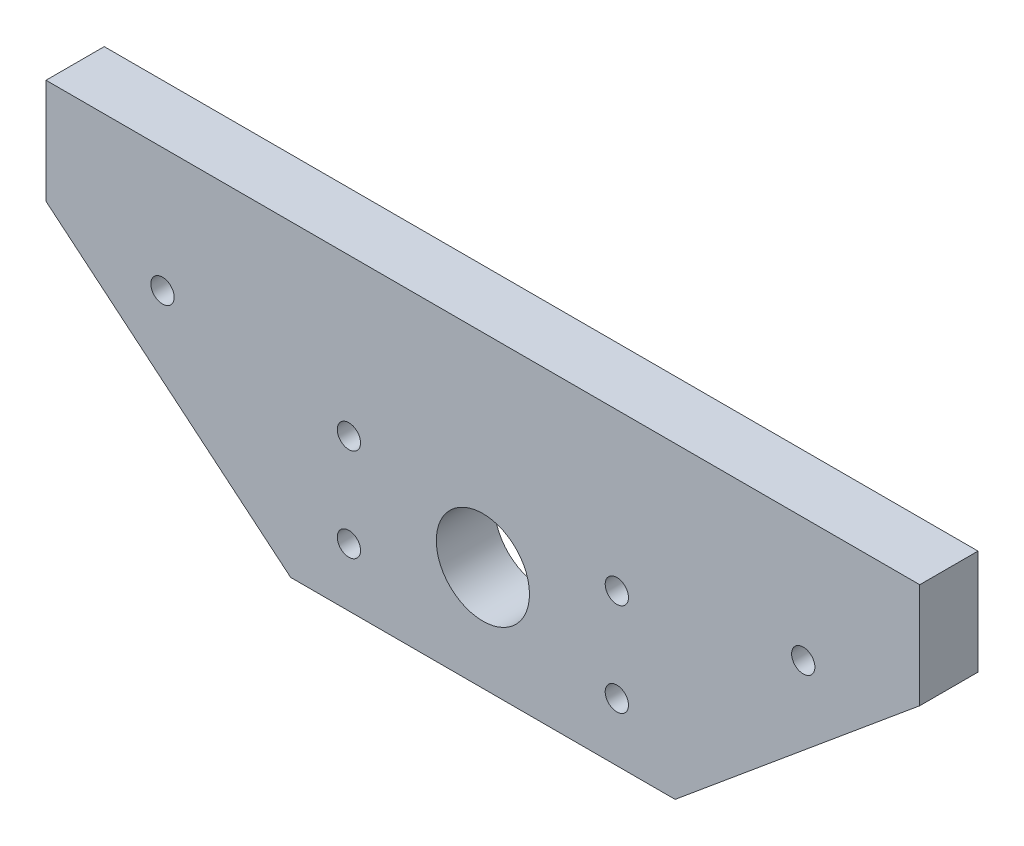
SolidWorks part; units mm, degrees
material "아크릴(내충격성)"
ref_plane "정면" through (0, 0, 0) normal (0, 0, 1) x (1, 0, 0)
ref_plane "윗면" through (0, 0, 0) normal (0, 1, 0) x (1, 0, 0)
ref_plane "우측면" through (0, 0, 0) normal (1, 0, 0) x (0, 0, -1)
sketch "스케치1" plane through (0, 0, 0) normal (0, 0, 1) x (1, 0, 0)
  line L1 (-75, 34.9192) -> (75, 34.9192)
  line L2 (-75, 34.9192) -> (-75, -35.0808)
  line L3 (-75, -35.0808) -> (75, -35.0808)
  line L4 (75, 34.9192) -> (75, -35.0808)
  line L5 (-75, 34.9192) -> (75, -35.0808) construction
  line L6 (-75, -35.0808) -> (75, 34.9192) construction
  dimension "D1" = 150
  dimension "D2" = 70
extrude "보스-돌출1" add sketch "스케치1" along normal blind 10
sketch "스케치2" plane through (0, 0, 10) normal (0, 0, 1) x (1, 0, 0)
  line L0 (75, 34.9192) -> (-75, 34.9192) construction
  line L1 (75, -35.0808) -> (75, 34.9192) construction
  line L2 (-75, -35.0808) -> (75, -35.0808) construction
  circle A0 centre (0, 0) radius 8
extrude "컷-돌출1" cut sketch "스케치2" against normal through all
sketch "스케치3" plane through (0, 0, 10) normal (0, 0, 1) x (1, 0, 0)
  line L0 (-56.0789, 0) -> (55.5902, 0) construction
  line L1 (0, 49.5425) -> (0, -49.6646) construction
  line L2 (-56.0789, -15) -> (55.5902, -15)
  line L3 (-56.0789, 15) -> (55.5902, 15)
  line L4 (-30, 49.5425) -> (-30, -49.6646)
  line L5 (30, 49.5425) -> (30, -49.6646)
  line L6 (75, 34.9192) -> (-75, 34.9192) construction
  circle A0 centre (-23, 8) radius 2
  circle A1 centre (-23, -8) radius 2
  circle A2 centre (23, -8) radius 2
  circle A3 centre (23, 8) radius 2
  dimension "D5" = 4
  dimension "D6" = 7
  dimension "D7" = 7
  dimension "D1" = 15
  dimension "D2" = 15
  dimension "D3" = 30
  dimension "D4" = 30
extrude "컷-돌출2" cut sketch "스케치3" against normal through all contours A0 | A1 | A2 | A3
sketch "스케치4" plane through (0, 0, 10) normal (0, 0, 1) x (1, 0, 0)
  line L0 (0, 49.097) -> (0, -61.2799) construction
  line L1 (-75, 34.9192) -> (-75, -35.0808) construction
  line L2 (-75, -35.0808) -> (75, -35.0808) construction
  line L3 (75, 34.9192) -> (-75, 34.9192) construction
  circle A0 centre (-55, 13.649) radius 2
  circle A1 centre (-65, -25.0808) radius 2
  circle A2 centre (65, -25.0808) radius 2
  circle A3 centre (55, 13.649) radius 2
  dimension "D1" = 4
  dimension "D2" = 4
  dimension "D3" = 10
  dimension "D4" = 10
  dimension "D5" = 20
  dimension "D6" = 40
extrude "컷-돌출3" cut sketch "스케치4" against normal through all
sketch "스케치5" plane through (0, 0, 10) normal (0, 0, 1) x (1, 0, 0)
  line L0 (-56.981, 13.9238) -> (56.981, 13.9238) construction
  line L1 (-65, -27.0808) -> (65, -27.0808) construction
  line L2 (-45, 25.7976) -> (-45, -31.7862) construction
  line L3 (-33, 24.5979) -> (-33, -29.3868) construction
  line L4 (33, 24.5979) -> (33, -29.3868) construction
  line L5 (45, 24.5979) -> (45, -30.7579) construction
  line L6 (-75, 16.9192) -> (-33, -18)
  line L16 (-75, 34.9192) -> (-75, -35.0808) construction
  line L18 (75, -35.0808) -> (75, 34.9192) construction
  line L19 (75, 16.9192) -> (75, -35.0808)
  line L20 (75, -35.0808) -> (-75, -35.0808)
  line L21 (-75, -35.0808) -> (-75, -27.0808)
  line L22 (75, 16.9192) -> (33, -18)
  line L23 (-75, 16.9192) -> (-75, -27.0808)
  line L25 (-33, -18) -> (33, -18)
  line L26 (-23, 8) -> (-23, 13.9238) construction
  line L27 (-56.981, 13.9238) -> (-23, 13.9238) construction
  circle A0 centre (-55, 13.649) radius 2 construction
  circle A1 centre (55, 13.649) radius 2 construction
  circle A2 centre (-23, -8) radius 2 construction
  circle A4 centre (65, -25.0808) radius 2 construction
  circle A5 centre (-23, 8) radius 2 construction
  circle A6 centre (23, 8) radius 2 construction
  point P9 (-65, -27.0808)
  dimension "D1" = 10
  dimension "D3" = 10
  dimension "D5" = 10
  dimension "D2" = 10
  dimension "D4" = 10
extrude "컷-돌출4" cut sketch "스케치5" against normal through all
